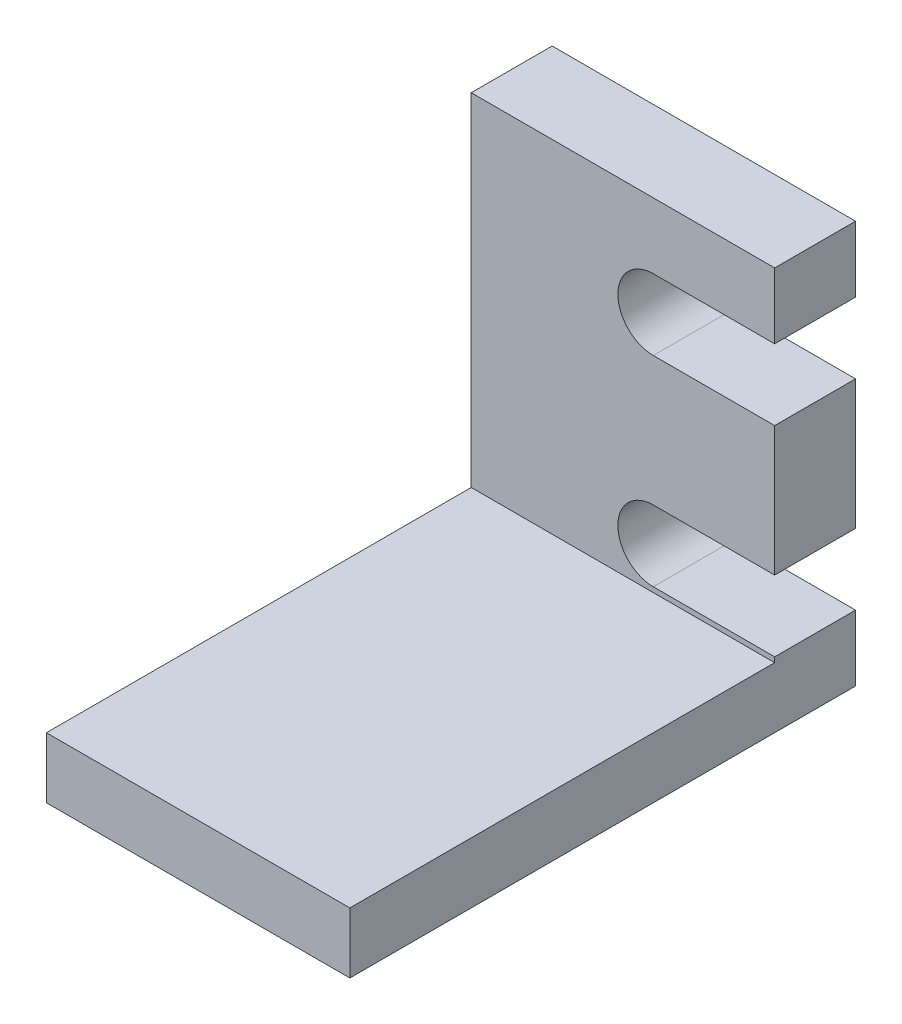
SolidWorks part; units mm, degrees
ref_plane "Piano frontale" through (0, 0, 0) normal (0, 0, 1) x (1, 0, 0)
ref_plane "Piano superiore" through (0, 0, 0) normal (0, 1, 0) x (1, 0, 0)
ref_plane "Piano destro" through (0, 0, 0) normal (1, 0, 0) x (0, 0, -1)
sketch "Schizzo1" plane through (0, 0, 0) normal (0, 0, 1) x (1, 0, 0)
  line L0 (0, 0) -> (0, 19.9)
  line L1 (0, 0) -> (15, 0)
  line L2 (0, 19.9) -> (15, 19.9)
  line L3 (15, 0) -> (15, 19.9)
  line L4 (15, 9.95) -> (12, 9.95) construction
  line L5 (12, 9.95) -> (12, 14.9) construction
  line L6 (12, 9.95) -> (12, 5) construction
  line L7 (9, 5) -> (15, 5) construction
  line L8 (9, 6.75) -> (15, 6.75)
  line L9 (9, 3.25) -> (15, 3.25)
  line L10 (9, 6.75) -> (9, 3.25) construction
  line L11 (9, 14.9) -> (15, 14.9) construction
  line L12 (9, 16.65) -> (15, 16.65)
  line L13 (9, 13.15) -> (15, 13.15)
  line L14 (9, 16.65) -> (9, 13.15) construction
  arc A0 (9, 6.75) -> (9, 3.25) centre (9, 5) ccw
  arc A1 (15, 3.25) -> (15, 6.75) centre (15, 5) ccw
  arc A2 (9, 16.65) -> (9, 13.15) centre (9, 14.9) ccw
  arc A3 (15, 13.15) -> (15, 16.65) centre (15, 14.9) ccw
  point P11 (12, 5)
  point P20 (12, 14.9)
extrude "Estrusione-Estrusione1" add sketch "Schizzo1" along normal blind 4 contours A2 L12 L3 L2 L0 L1 L9 A0 L8 L13
sketch "Schizzo2" plane through (0, 0, 4) normal (0, 0, 1) x (1, 0, 0)
  line L0 (0, 0) -> (15, 0)
  line L1 (0, 0) -> (0, 3)
  line L2 (15, 0) -> (15, 3)
  line L3 (0, 3) -> (15, 3)
extrude "Estrusione-Estrusione2" add sketch "Schizzo2" along normal blind 21
